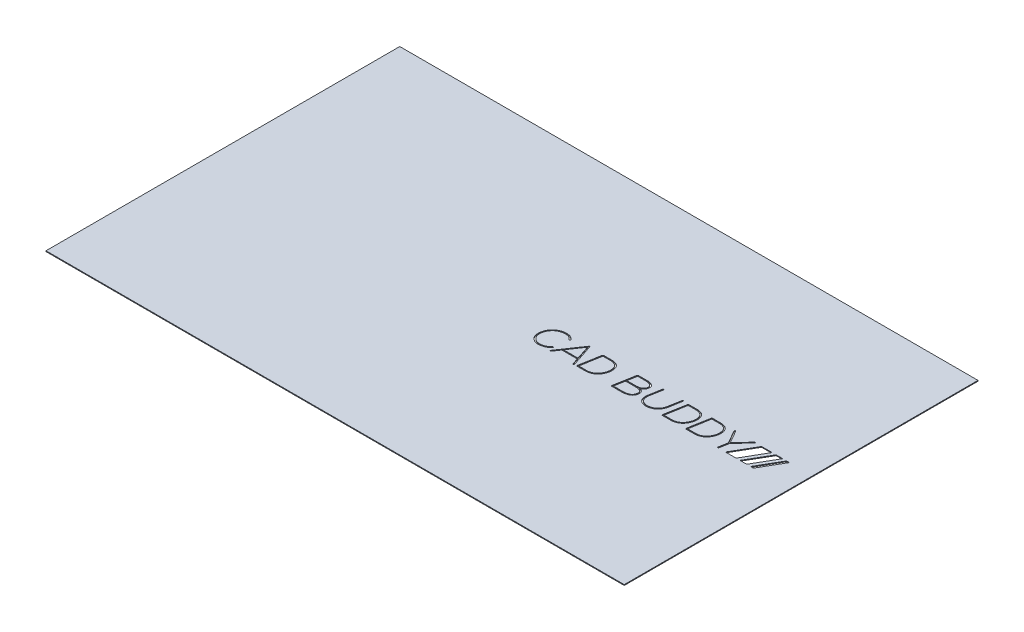
SolidWorks part; units mm, degrees
material "Neutron Star"
ref_plane "Front Plane" through (0, 0, 0) normal (0, 0, 1) x (1, 0, 0)
ref_plane "Top Plane" through (0, 0, 0) normal (0, 1, 0) x (1, 0, 0)
ref_plane "Right Plane" through (0, 0, 0) normal (1, 0, 0) x (0, 0, -1)
sketch "Sketch1" plane through (0, 0, 0) normal (0, 1, 0) x (1, 0, 0)
  line L0 (0, 0) -> (743.0712, 0) construction
  line L1 (743.0712, 0) -> (743.0712, 75.433) construction
  line L2 (743.0712, 0) -> (1070.0896, 0) construction
  line L3 (743.0712, 75.433) -> (1070.0896, 75.433) construction
  line L4 (743.0712, 0) -> (786.6225, 75.433)
  line L5 (786.6225, 75.433) -> (821.5475, 75.433)
  line L6 (821.5475, 75.433) -> (777.9962, 0)
  line L7 (777.9962, 0) -> (743.0712, 0)
  line L8 (790.6962, 0) -> (834.2475, 75.433)
  line L9 (834.2475, 75.433) -> (856.4725, 75.433)
  line L10 (856.4725, 75.433) -> (812.9212, 0)
  line L11 (812.9212, 0) -> (790.6962, 0)
  line L12 (869.1725, 75.433) -> (825.6212, 0)
  line L13 (825.6212, 0) -> (835.1462, 0)
  line L14 (835.1462, 0) -> (878.6975, 75.433)
  line L15 (878.6975, 75.433) -> (869.1725, 75.433)
  line L16 (878.6975, 75.433) -> (0, 75.433) construction
  line L17 (0, 75.433) -> (0, 0) construction
  line L18 (878.6975, 75.433) -> (0, 0) construction
  line L19 (954.61, 242.3836) -> (954.61, 620.4145)
  line L20 (-75.9125, 242.3836) -> (954.61, 242.3836)
  line L21 (-75.9125, 242.3836) -> (-75.9125, -166.9506)
  line L22 (-75.9125, -166.9506) -> (954.61, -166.9506)
  line L23 (954.61, 242.3836) -> (954.61, -166.9506)
  line L24 (-75.9125, 242.3836) -> (954.61, -166.9506) construction
  line L25 (-75.9125, -166.9506) -> (954.61, 242.3836) construction
  line L26 (954.61, 620.4145) -> (-950.39, 620.4145)
  line L27 (-950.39, 620.4145) -> (-950.39, -544.9815)
  line L28 (-950.39, -544.9815) -> (954.61, -544.9815)
  line L29 (954.61, -544.9815) -> (954.61, -166.9506)
  text T0 "CAD BUDDY" font "Hero Light" height 76.2
  point P15 (439.3488, 37.7165)
  dimension "D1" = 34.925
  dimension "D2" = 22.225
  dimension "D3" = 60
  dimension "D4" = 9.525
  dimension "D5" = 12.7
  dimension "D6" = 12.7
  dimension "D7" = 1030.5224
  dimension "D8" = 1905
extrude "Boss-Extrude1" add sketch "Sketch1" along normal blind 2.54 contours L23 L20 L21 L22 L15 L14 L13 L12 L6 L7 L4 L5 L10 L11 L8 L9 | L28 L29 L22 L21 L20 L19 L26 L27
sketch "Sketch3" plane through (0, 2.54, 0) normal (0, 1, 0) x (1, 0, 0)
  line L0 (914.9972, 0) -> (-75.9125, 0) construction
  text T0 "CAD BUDDY" font "Hero Light" height 76.2
  point P2 (885.3111, 0)
  point P3 (0, 0)
  point P8 (0, 0)
  point P9 (893.4031, 0)
  point P10 (914.9972, 0)
  point P11 (0, 0)
  dimension "D1" = 76.2
extrude "Cut-Extrude1" cut sketch "Sketch3" against normal blind 2.54
